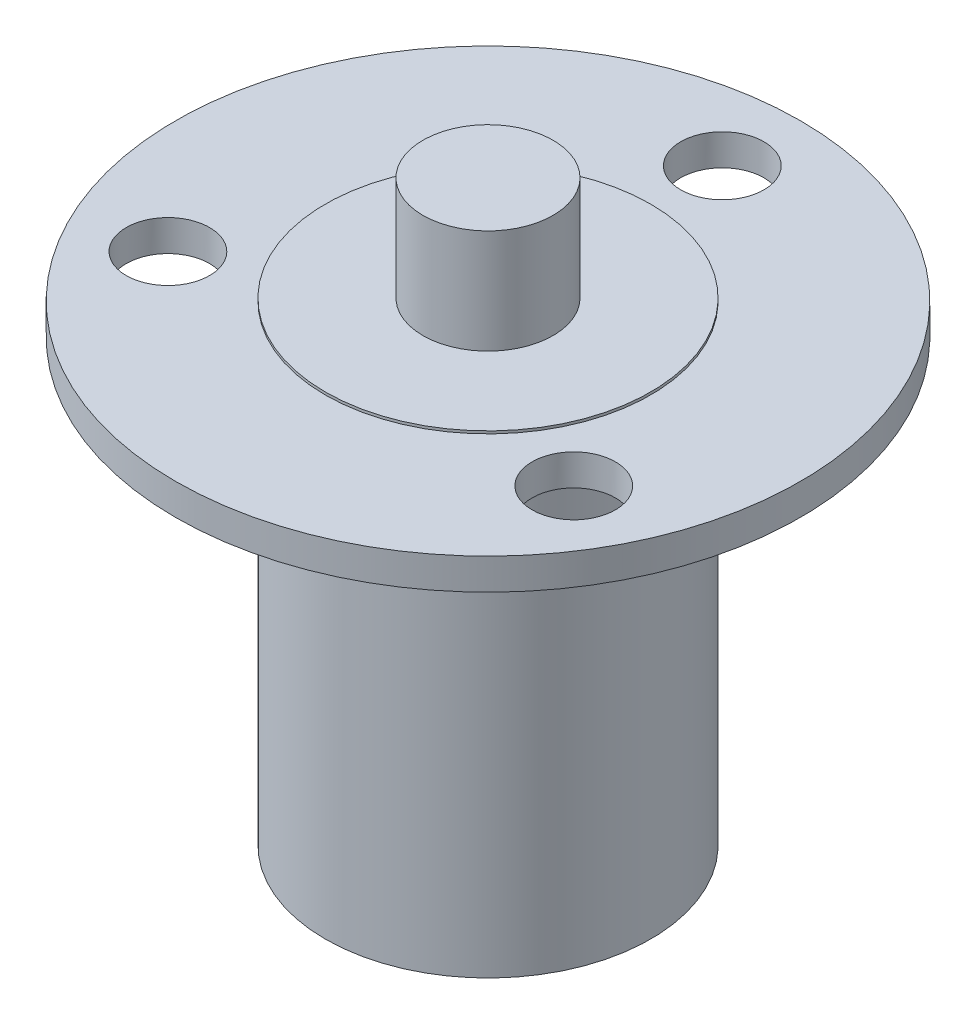
SolidWorks part; units mm, degrees
ref_plane "前视基准面" through (0, 0, 0) normal (0, 0, 1) x (1, 0, 0)
ref_plane "上视基准面" through (0, 0, 0) normal (0, 1, 0) x (1, 0, 0)
ref_plane "右视基准面" through (0, 0, 0) normal (1, 0, 0) x (0, 0, -1)
sketch "草图1" plane through (0, 0, 0) normal (0, 0, 1) x (1, 0, 0)
  line L0 (12, 18.1) -> (0, 18.1)
  line L1 (0, 18.1) -> (0, 16.9)
  line L2 (0, 16.9) -> (12, 16.9)
  line L3 (12, 16.9) -> (12, 18.1)
  line L4 (0, 18.1) -> (0, 16.9) construction
revolve "旋转1" add sketch "草图1" angle 360 about L4
sketch "草图2" plane through (0, 18.1, 0) normal (0, 1, 0) x (-1, 0, 0)
  circle A0 centre (0, 0) radius 6.25
extrude "凸台-拉伸1" add sketch "草图2" along normal blind 0.1
sketch "草图3" plane through (0, 18.2, 0) normal (0, 1, 0) x (-1, 0, 0)
  circle A0 centre (0, 0) radius 2.5
extrude "凸台-拉伸2" add sketch "草图3" along normal blind 4
sketch "草图4" plane through (0, 22.2, 0) normal (0, 1, 0) x (-1, 0, 0)
  circle A0 centre (0, 0) radius 0.4581
sketch "草图5" plane through (0, 16.9, 0) normal (0, -1, 0) x (1, 0, 0)
  circle A0 centre (0, 0) radius 6.25
extrude "凸台-拉伸4" add sketch "草图5" along normal blind 16.9
ref_plane "基准面4" through (0, 0, -1.0582) normal (0, 0, 1) x (1, 0, 0)
hole_wizard "Ø3.2 (3.2) 直径孔1" positions "草图22" profile "草图21" hole size "Ø3.2" standard "ANSI Metric"
sketch "草图22" plane through (0, 18.1, 0) normal (0, 1, 0) x (1, 0, 0)
  point P0 (-7.7942, -4.5)
  point P1 (7.7942, -4.5)
  point P2 (0, 9)
sketch "草图21" plane through (-7.7942, 18.1, 4.5) normal (1, 0, 0) x (0, 0, 1)
  line L0 (0, 0) -> (0, 18.1)
  line L1 (0, 18.1) -> (1.6, 18.1)
  line L2 (1.6, 18.1) -> (1.6, 0)
  line L5 (1.6, 0) -> (0, 0)
  line L11 (0, -6.35) -> (0, 107.95) construction
  dimension "通孔孔直径" = 3.2
  dimension "通孔孔深度" = 18.1
